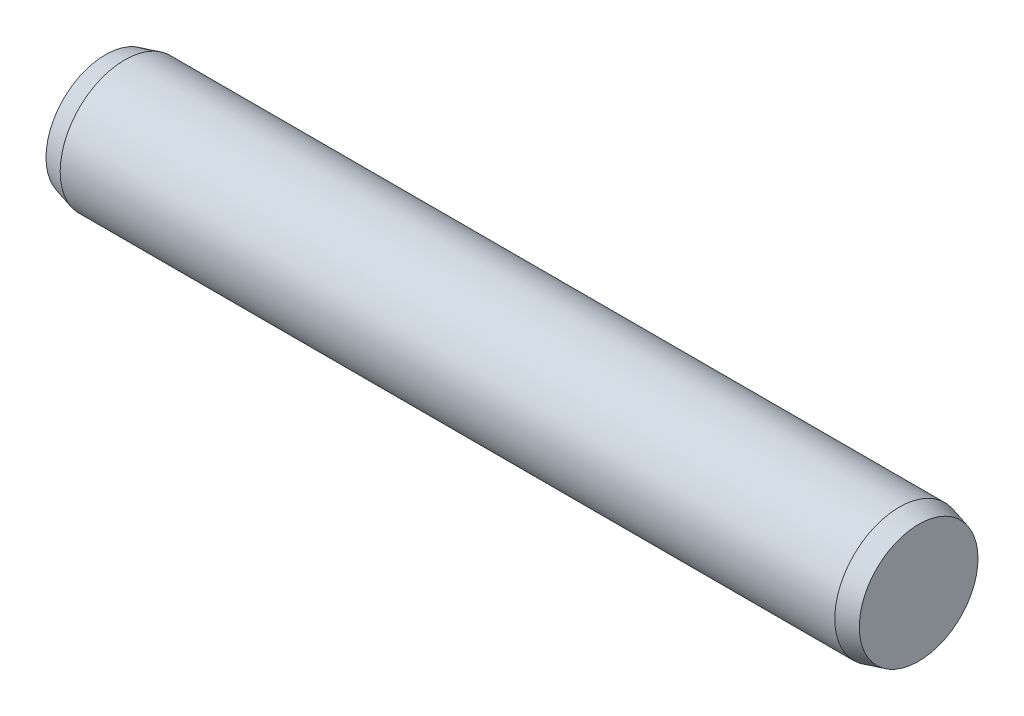
SolidWorks part; units mm, degrees
ref_plane "Front Plane" through (0, 0, 0) normal (0, 0, 1) x (1, 0, 0)
ref_plane "Top Plane" through (0, 0, 0) normal (0, 1, 0) x (1, 0, 0)
ref_plane "Right Plane" through (0, 0, 0) normal (1, 0, 0) x (0, 0, -1)
sketch "Sketch1" plane through (0, 0, 0) normal (0, 0, 1) x (1, 0, 0)
  line L0 (-9, 0) -> (9, 0) construction
  line L1 (9, 1.5) -> (9, -1.5) construction
  line L2 (-9, 1.5) -> (-9, -1.5) construction
  line L3 (9.45, 1.5) -> (9.45, -1.5) construction
  line L4 (-9.45, 1.5) -> (-9.45, -1.5) construction
  line L5 (-9, 0) -> (-9.45, 0) construction
  line L6 (9, 0) -> (9.45, 0) construction
  dimension "D1" = 0.45
  dimension "Dia" = 3
  dimension "Length" = 18
  dimension "C" = 0.45
sketch "Sketch2" plane through (0, 0, 0) normal (1, 0, 0) x (0, 0, -1)
  circle A0 centre (0, 0) radius 1.5
extrude "Extrude1" add sketch "Sketch2" against normal up to vertex (9 mm away) and the other way up to vertex (9 mm away) up to point (-9, 1.5, 0) other way up to point (9, 1.5, 0)
sketch "Sketch3" plane through (9, 0, 0) normal (1, 0, 0) x (0, 0, -1)
  circle A1 centre (0, 0) radius 1.5
  circle A2 centre (0, 0) radius 1.5
  dimension "D1" = 0
extrude "Extrude2" add sketch "Sketch3" along normal up to vertex (0.45 mm away) draft 15 up to point (9.45, 0, 0)
sketch "Sketch4" plane through (-9, 0, 0) normal (-1, 0, 0) x (0, 0, 1)
  circle A1 centre (0, 0) radius 1.5
  circle A2 centre (0, 0) radius 1.5
  dimension "D1" = 0
extrude "Extrude3" add sketch "Sketch4" along normal up to vertex (0.45 mm away) draft 15 up to point (-9.45, 0, 0)
equation "\"D1@Sketch1\" = \"C@Sketch1\""
